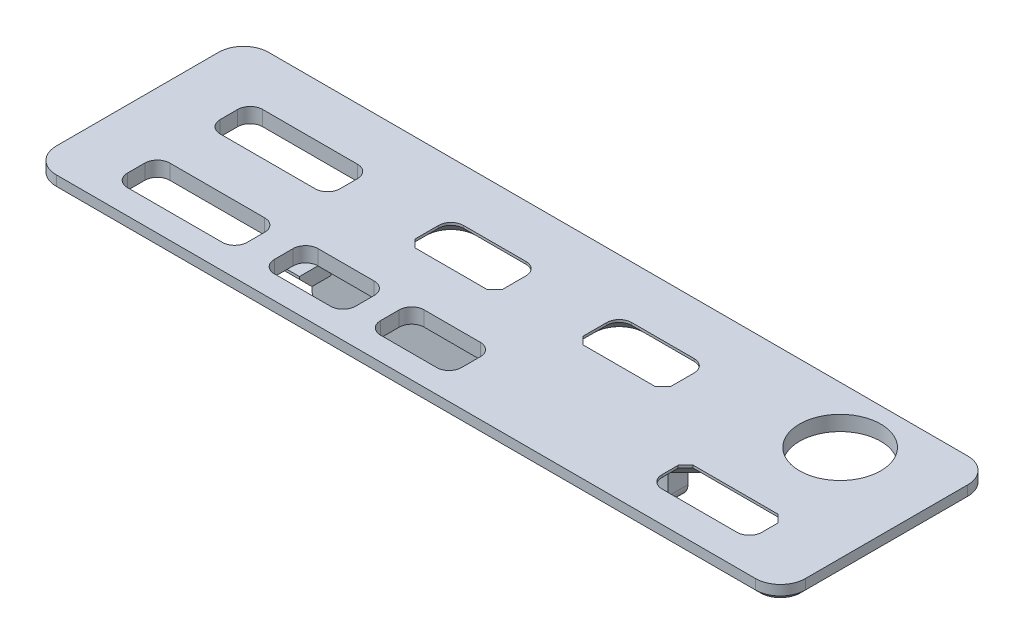
SolidWorks part; units mm, degrees
ref_plane "前视基准面" through (0, 0, 0) normal (0, 0, 1) x (1, 0, 0)
ref_plane "上视基准面" through (0, 0, 0) normal (0, 1, 0) x (1, 0, 0)
ref_plane "右视基准面" through (0, 0, 0) normal (1, 0, 0) x (0, 0, -1)
sketch "草图1" plane through (0, 0, 0) normal (0, 1, 0) x (1, 0, 0)
  line L1 (-30, 8.5) -> (30, 8.5)
  line L2 (-30, 8.5) -> (-30, -8.5)
  line L3 (-30, -8.5) -> (30, -8.5)
  line L4 (30, 8.5) -> (30, -8.5)
  line L5 (-30, 8.5) -> (30, -8.5) construction
  line L6 (-30, -8.5) -> (30, 8.5) construction
  point P0 (0, 0)
  dimension "D1" = 60
  dimension "D2" = 17
extrude "凸台-拉伸1" add sketch "草图1" along normal blind 1.2
sketch "草图4" plane through (0, 1.2, 0) normal (0, 1, 0) x (1, 0, 0)
  line L0 (-30, 8.5) -> (-30, -8.5) construction
  line L1 (-25.2717, 4.3) -> (-15.6717, 4.3)
  line L2 (-25.2717, 4.3) -> (-25.2717, 0.9)
  line L3 (-25.2717, 0.9) -> (-15.6717, 0.9)
  line L4 (-15.6717, 4.3) -> (-15.6717, 0.9)
  line L5 (-9.1829, 4.3) -> (-2.1829, 4.3)
  line L6 (-9.1829, 4.3) -> (-9.1829, 0.8)
  line L7 (-9.1829, 0.8) -> (-2.1829, 0.8)
  line L8 (-2.1829, 4.3) -> (-2.1829, 0.8)
  line L9 (4.2885, 4.3) -> (11.2885, 4.3)
  line L10 (4.2885, 4.3) -> (4.2885, 0.8)
  line L11 (4.2885, 0.8) -> (11.2885, 0.8)
  line L12 (11.2885, 4.3) -> (11.2885, 0.8)
  line L13 (17.05, -3.1348) -> (25.05, -3.1348)
  line L14 (17.05, -3.1348) -> (17.05, -6.0348)
  line L15 (17.05, -6.0348) -> (25.05, -6.0348)
  line L16 (25.05, -3.1348) -> (25.05, -6.0348)
  line L17 (-4.9, -3.1348) -> (1.6, -3.1348)
  line L18 (-4.9, -3.1348) -> (-4.9, -6.6348)
  line L19 (-4.9, -6.6348) -> (1.6, -6.6348)
  line L20 (1.6, -3.1348) -> (1.6, -6.6348)
  line L21 (-13.4, -3.1348) -> (-6.9, -3.1348)
  line L22 (-13.4, -3.1348) -> (-13.4, -6.6348)
  line L23 (-13.4, -6.6348) -> (-6.9, -6.6348)
  line L24 (-6.9, -3.1348) -> (-6.9, -6.6348)
  line L25 (-25.2717, -3.1348) -> (-15.6717, -3.1348)
  line L26 (-25.2717, -3.1348) -> (-25.2717, -6.5348)
  line L27 (-25.2717, -6.5348) -> (-15.6717, -6.5348)
  line L28 (-15.6717, -3.1348) -> (-15.6717, -6.5348)
  line L29 (30, 8.5) -> (-30, 8.5) construction
  line L31 (30, -8.5) -> (30, 8.5) construction
  line L32 (30, 8.5) -> (-30, 8.5) construction
  circle A0 centre (22.2985, 3.9832) radius 3.25
  dimension "D21" = 6.5
  dimension "D1" = 3.5
  dimension "D2" = 6.5
  dimension "D3" = 6.5
  dimension "D4" = 3.5
  dimension "D5" = 9.6
  dimension "D6" = 3.4
  dimension "D7" = 7
  dimension "D8" = 8
  dimension "D9" = 2.9
  dimension "D10" = 4.7283
  dimension "D11" = 7.6
  dimension "D12" = 11.6348
  dimension "D13" = 16.6
  dimension "D14" = 25.1
  dimension "D15" = 4.95
  dimension "D16" = 7
  dimension "D17" = 20.8171
  dimension "D18" = 34.2885
  dimension "D19" = 7.7015
  dimension "D20" = 4.5168
  dimension "D22" = 3.5
extrude "切除-拉伸1" cut sketch "草图4" against normal up to next
fillet "圆角2" radius 1 22 edges at (-25.2717, 0.6, -0.9) (-25.2717, 0.6, -4.3) (-15.6717, 0.6, -0.9) (-15.6717, 0.6, -4.3) (-2.1829, 0.6, -4.3) (-9.1829, 0.6, -4.3) (4.2885, 0.6, -4.3) (11.2885, 0.6, -4.3) (25.05, 0.6, 6.0348) (17.05, 0.6, 6.0348) (1.6, 0.6, 6.6348) (1.6, 0.6, 3.1348) (-4.9, 0.6, 3.1348) (-4.9, 0.6, 6.6348) (-6.9, 0.6, 6.6348) (-6.9, 0.6, 3.1348) (-13.4, 0.6, 3.1348) (-13.4, 0.6, 6.6348) (-15.6717, 0.6, 6.5348) (-15.6717, 0.6, 3.1348) (-25.2717, 0.6, 3.1348) (-25.2717, 0.6, 6.5348)
chamfer "倒角1" distance 0.6 angle 45 6 edges at (-9.1829, 0.6, -0.8) (-2.1829, 0.6, -0.8) (4.2885, 0.6, -0.8) (11.2885, 0.6, -0.8) (17.05, 0.6, 3.1348) (25.05, 0.6, 3.1348)
sketch "草图5" plane through (0, 0, 0) normal (0, -1, 0) x (1, 0, 0)
  line L0 (-30, -8.5) -> (-30, 8.5) construction
  line L1 (-13.9089, -3.3832) -> (-12.4089, -3.3832)
  line L2 (-13.9089, -3.3832) -> (-13.9089, 4.6168)
  line L3 (-13.9089, 4.6168) -> (-12.4089, 4.6168)
  line L4 (-12.4089, -3.3832) -> (-12.4089, 4.6168)
  line L5 (13.0911, -3.3832) -> (14.5911, -3.3832)
  line L6 (13.0911, -3.3832) -> (13.0911, 4.6168)
  line L7 (13.0911, 4.6168) -> (14.5911, 4.6168)
  line L8 (14.5911, -3.3832) -> (14.5911, 4.6168)
  line L9 (30, -8.5) -> (-30, -8.5) construction
  line L10 (30, 8.5) -> (30, -8.5) construction
  dimension "D1" = 1.5
  dimension "D2" = 8
  dimension "D3" = 1.5
  dimension "D4" = 8
  dimension "D5" = 16.0911
  dimension "D6" = 5.1168
  dimension "D7" = 5.1168
  dimension "D8" = 15.4089
extrude "凸台-拉伸2" add sketch "草图5" along normal blind 1.2
sketch "草图6" plane through (0, 0, 0) normal (0, -1, 0) x (1, 0, 0)
  line L0 (-13.9089, 4.6168) -> (-13.9089, -3.3832) construction
  line L1 (-13.9089, 2.1) -> (14.5911, 2.1)
  line L2 (-13.9089, 2.1) -> (-13.9089, 0.5)
  line L3 (-13.9089, 0.5) -> (14.5911, 0.5)
  line L4 (14.5911, 2.1) -> (14.5911, 0.5)
  line L5 (30, -8.5) -> (-30, -8.5) construction
  dimension "D1" = 1.6
  dimension "D2" = 9
extrude "凸台-拉伸3" add sketch "草图6" along normal blind 4
fillet "圆角3" radius 1 2 edges at (14.5911, -4, 1.3) (-13.9089, -4, 1.3)
chamfer "倒角2" distance 1 angle 45 4 edges at (13.8411, -1.2, -3.3832) (-13.1589, -1.2, -3.3832) (13.8411, -1.2, 4.6168) (-13.1589, -1.2, 4.6168)
chamfer "倒角4" distance 1 angle 45 24 edges at (11.2885, 0, -2.35) (10.9956, 0, -4.0071) (7.7885, 0, -4.3) (4.5814, 0, -4.0071) (10.9885, 0, -1.1) (4.2885, 0, -2.35) (4.5885, 0, -1.1) (7.7885, 0, -0.8) (-9.1829, 0, -2.35) (-2.1829, 0, -2.35) (-8.89, 0, -4.0071) (-2.4758, 0, -4.0071) (-5.6829, 0, -4.3) (-2.4829, 0, -1.1) (-8.8829, 0, -1.1) (-5.6829, 0, -0.8) (17.35, 0, 3.4348) (21.05, 0, 3.1348) (24.75, 0, 3.4348) (25.05, 0, 4.3848) (17.05, 0, 4.3848) (24.7571, 0, 5.7419) (17.3429, 0, 5.7419) (21.05, 0, 6.0348)
fillet "圆角4" radius 2 4 edges at (30, 0.6, 8.5) (30, 0.6, -8.5) (-30, 0.6, 8.5) (-30, 0.6, -8.5)
chamfer "倒角5" distance 0.4 angle 45 8 edges at (0, 0, -8.5) (-29.4142, 0, -7.9142) (29.4142, 0, -7.9142) (-30, 0, 0) (30, 0, 0) (-29.4142, 0, 7.9142) (29.4142, 0, 7.9142) (0, 0, 8.5)
